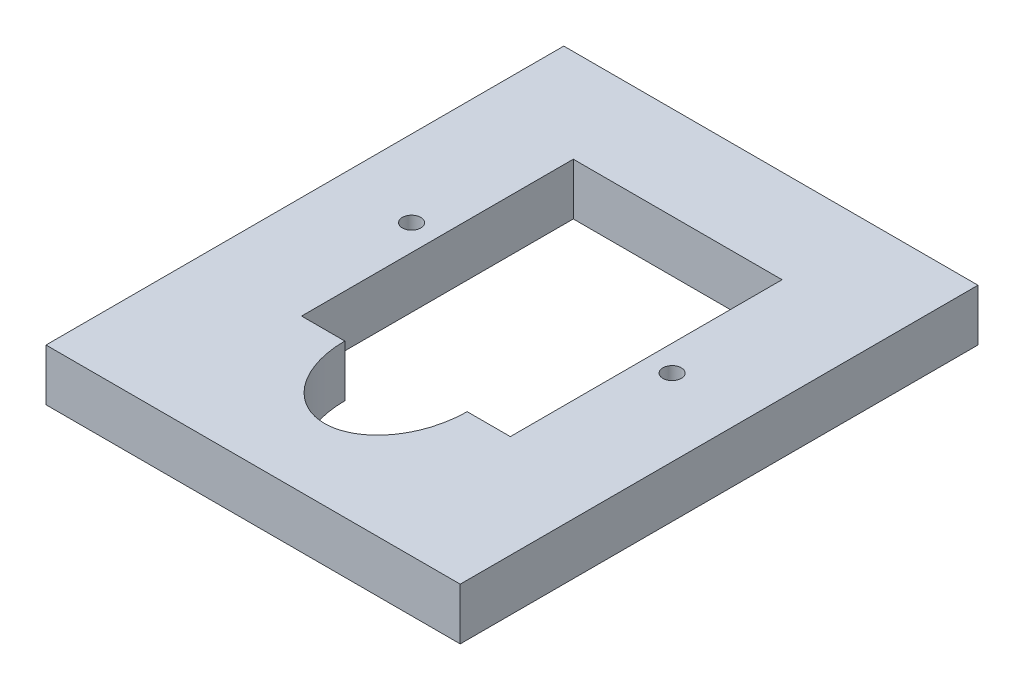
SolidWorks part; units mm, degrees
ref_plane "Front Plane" through (0, 0, 0) normal (0, 0, 1) x (1, 0, 0)
ref_plane "Top Plane" through (0, 0, 0) normal (0, 1, 0) x (1, 0, 0)
ref_plane "Right Plane" through (0, 0, 0) normal (1, 0, 0) x (0, 0, -1)
sketch "Sketch1" plane through (0, 0, 0) normal (0, 1, 0) x (1, 0, 0)
  line L0 (21.7665, 29.8808) -> (21.7665, -33.6192) construction
  line L1 (-3.6335, 29.8808) -> (47.1665, 29.8808)
  line L2 (-3.6335, 29.8808) -> (-3.6335, -33.6192)
  line L3 (-3.6335, -33.6192) -> (47.1665, -33.6192)
  line L4 (47.1665, 29.8808) -> (47.1665, -33.6192)
  line L5 (29.2665, -14.874) -> (34.5681, -14.874)
  line L6 (8.9649, 18.4508) -> (34.5681, 18.4508)
  line L7 (8.9649, 18.4508) -> (8.9649, -14.874)
  line L8 (8.9649, -14.874) -> (14.2665, -14.874)
  line L9 (34.5681, 18.4508) -> (34.5681, -14.874)
  circle A0 centre (37.7431, 1.7884) radius 1.1303
  circle A1 centre (5.7899, 1.7884) radius 1.1303
  ellipse E0 centre (21.7665, -14.874) end of major axis (21.7665, -4.874) minor radius 7.5 (14.2665, -14.874) -> (29.2665, -14.874) ccw
  dimension "D11" = 2.2606
  dimension "D12" = 2.2606
  dimension "D13" = 10
  dimension "D1" = 50.8
  dimension "D2" = 63.5
  dimension "D3" = 33.3248
  dimension "D4" = 25.6032
  dimension "D5" = 11.43
  dimension "D6" = 12.8016
  dimension "D7" = 3.175
  dimension "D8" = 3.175
  dimension "D9" = 16.6624
  dimension "D10" = 16.6624
  dimension "D14" = 7.5
extrude "Boss-Extrude1" add sketch "Sketch1" along normal blind 6.35
